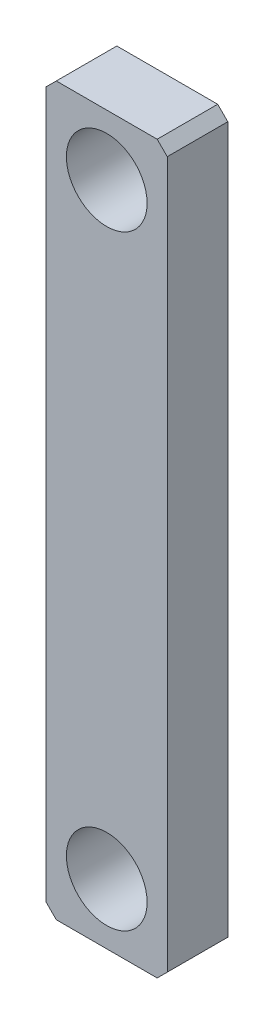
SolidWorks part; units mm, degrees
material "2024-T3"
ref_plane "正面" through (0, 0, 0) normal (0, 0, 1) x (1, 0, 0)
ref_plane "平面" through (0, 0, 0) normal (0, 1, 0) x (1, 0, 0)
ref_plane "右側面" through (0, 0, 0) normal (1, 0, 0) x (0, 0, -1)
sketch "ｽｹｯﾁ4" plane through (0, 0, 0) normal (0, 0, 1) x (1, 0, 0)
  line L1 (-6, 36) -> (6, 36)
  line L2 (-6, 36) -> (-6, -36)
  line L3 (-6, -36) -> (6, -36)
  line L4 (6, 36) -> (6, -36)
  line L5 (-6, 36) -> (6, -36) construction
  line L6 (-6, -36) -> (6, 36) construction
  point P0 (0, 0)
  dimension "D1" = 12
  dimension "D2" = 72
extrude "ﾎﾞｽ - 押し出し1" add sketch "ｽｹｯﾁ4" along normal blind 6
sketch "ｽｹｯﾁ5" plane through (0, 0, 6) normal (0, 0, 1) x (1, 0, 0)
  line L0 (6, 36) -> (-6, 36) construction
  line L1 (6, -36) -> (6, 36) construction
  line L2 (-6, -36) -> (6, -36) construction
  circle A0 centre (0, 30) radius 4
  circle A1 centre (0, -30) radius 4
  dimension "D5" = 8
  dimension "D6" = 8
  dimension "D1" = 6
  dimension "D2" = 6
  dimension "D3" = 6
  dimension "D4" = 6
extrude "ｶｯﾄ - 押し出し1" cut sketch "ｽｹｯﾁ5" against normal through all and the other way through all
chamfer "面取り1" distance 1 angle 45 4 edges at (6, -36, 3) (-6, -36, 3) (-6, 36, 3) (6, 36, 3)
